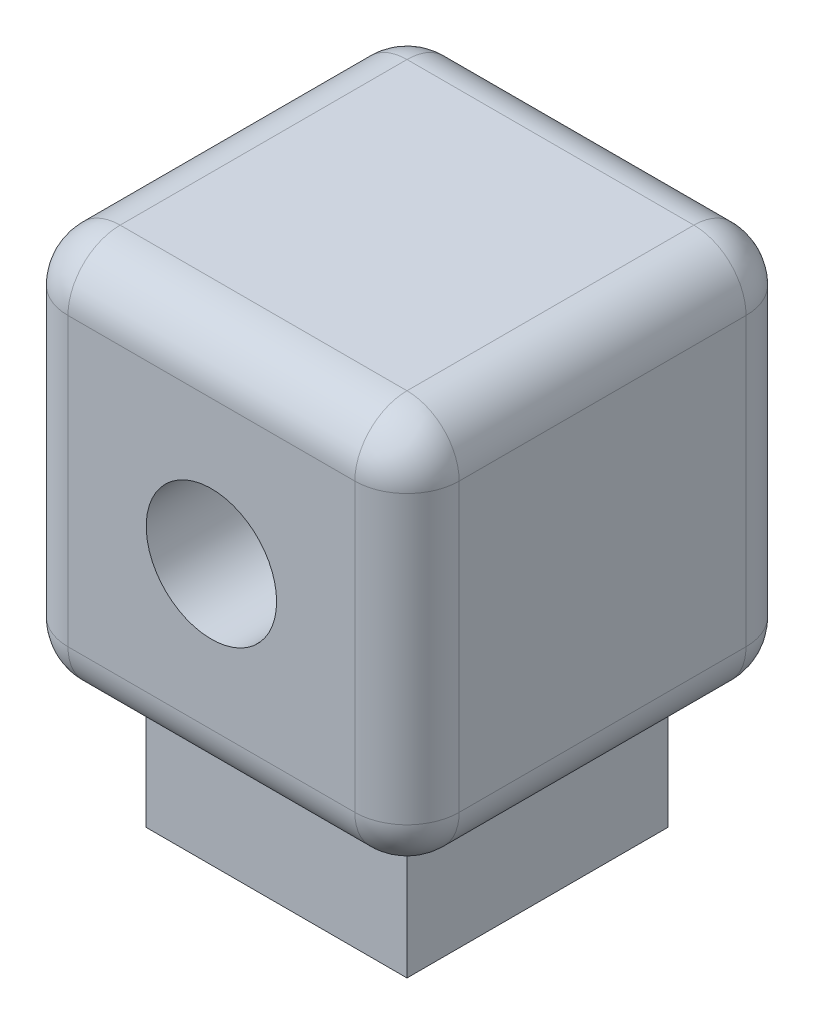
SolidWorks part; units mm, degrees
ref_plane "Front Plane" through (0, 0, 0) normal (0, 0, 1) x (1, 0, 0)
ref_plane "Top Plane" through (0, 0, 0) normal (0, 1, 0) x (1, 0, 0)
ref_plane "Right Plane" through (0, 0, 0) normal (1, 0, 0) x (0, 0, -1)
sketch "Sketch1" plane through (0, 0, 0) normal (0, 1, 0) x (1, 0, 0)
  line L1 (-2.0523, -10) -> (12.9477, -10)
  line L2 (-2.0523, -10) -> (-2.0523, 5)
  line L3 (-2.0523, 5) -> (12.9477, 5)
  line L4 (12.9477, -10) -> (12.9477, 5)
  line L5 (-2.0523, -10) -> (12.9477, 5) construction
  line L6 (-2.0523, 5) -> (12.9477, -10) construction
  point P1 (5.4477, -2.5)
  dimension "D1" = 15
  dimension "D2" = 15
extrude "Boss-Extrude1" add sketch "Sketch1" along normal blind 15
sketch "Sketch2" plane through (0, 0, 0) normal (0, -1, 0) x (1, 0, 0)
  line L0 (12.9477, -5) -> (-2.0523, -5) construction
  line L1 (0.4477, 7.5) -> (10.4477, 7.5)
  line L2 (0.4477, 7.5) -> (0.4477, -2.5)
  line L3 (0.4477, -2.5) -> (10.4477, -2.5)
  line L4 (10.4477, 7.5) -> (10.4477, -2.5)
  line L5 (0.4477, 7.5) -> (10.4477, -2.5) construction
  line L6 (0.4477, -2.5) -> (10.4477, 7.5) construction
  line L7 (12.9477, 10) -> (12.9477, -5) construction
  point P0 (5.4477, 2.5)
  dimension "D1" = 7.5
  dimension "D2" = 7.5
  dimension "D3" = 10
  dimension "D4" = 10
extrude "Boss-Extrude2" add sketch "Sketch2" along normal blind 5
sketch "Sketch3" plane through (0, 0, 10) normal (0, 0, 1) x (1, 0, 0)
  line L0 (-2.0523, 15) -> (-2.0523, 0) construction
  line L1 (-2.0523, 15) -> (12.9477, 15) construction
  circle A0 centre (5.4477, 7.5) radius 2.5
  dimension "D1" = 5
  dimension "D2" = 7.5
  dimension "D3" = 7.5
extrude "Cut-Extrude1" cut sketch "Sketch3" against normal through all
fillet "Fillet1" radius 2 12 edges at (-2.0523, 0, 2.5) (5.4477, 0, -5) (12.9477, 0, 2.5) (5.4477, 0, 10) (-2.0523, 7.5, 10) (-2.0523, 7.5, -5) (12.9477, 7.5, -5) (12.9477, 7.5, 10) (-2.0523, 15, 2.5) (5.4477, 15, 10) (12.9477, 15, 2.5) (5.4477, 15, -5)
